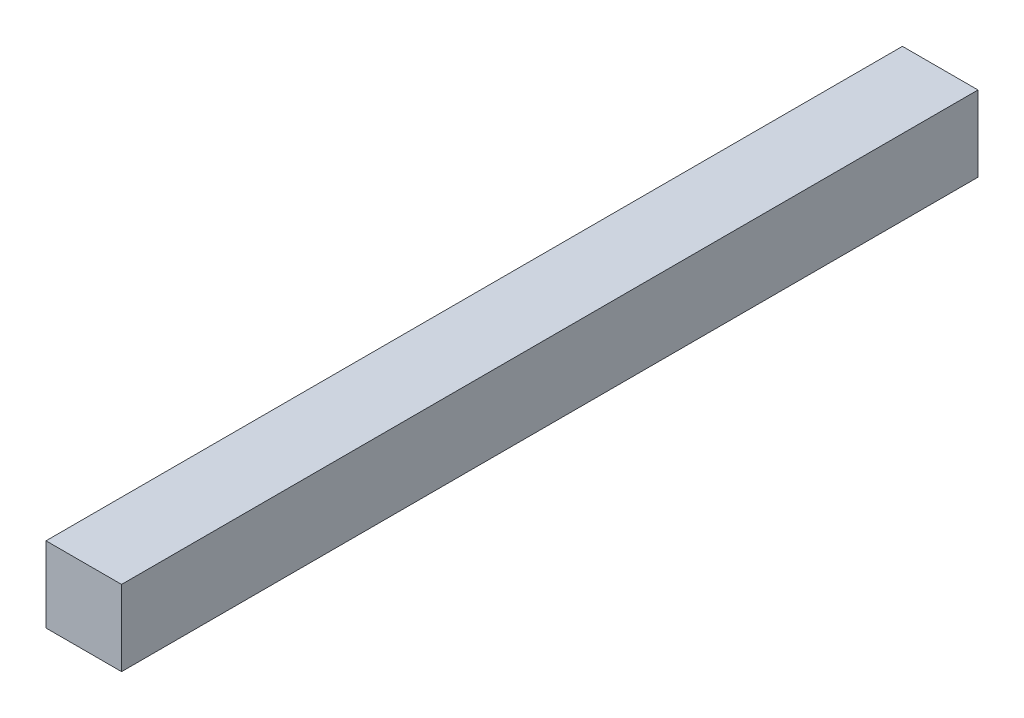
SolidWorks part; units mm, degrees
ref_plane "前视基准面" through (0, 0, 0) normal (0, 0, 1) x (1, 0, 0)
ref_plane "上视基准面" through (0, 0, 0) normal (0, 1, 0) x (1, 0, 0)
ref_plane "右视基准面" through (0, 0, 0) normal (1, 0, 0) x (0, 0, -1)
sketch "草图1" plane through (0, 0, 0) normal (0, 0, 1) x (1, 0, 0)
  line L1 (-15, 15) -> (15, 15)
  line L2 (-15, 15) -> (-15, -15)
  line L3 (-15, -15) -> (15, -15)
  line L4 (15, 15) -> (15, -15)
  line L5 (-15, 15) -> (15, -15) construction
  line L6 (-15, -15) -> (15, 15) construction
  point P0 (0, 0)
  dimension "D1" = 30
  dimension "D2" = 30
extrude "凸台-拉伸1" add sketch "草图1" along normal blind 340
